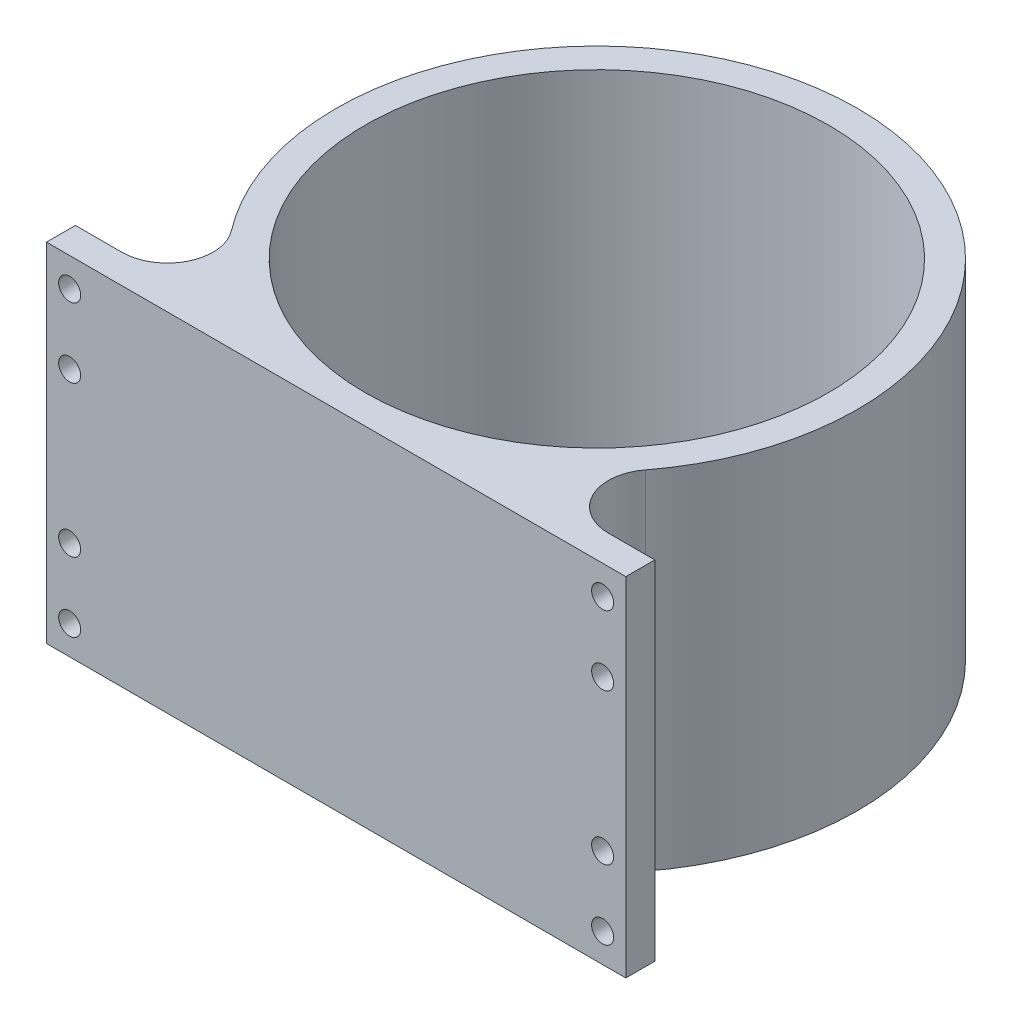
SolidWorks part; units mm, degrees
ref_plane "Front Plane" through (0, 0, 0) normal (0, 0, 1) x (1, 0, 0)
ref_plane "Top Plane" through (0, 0, 0) normal (0, 1, 0) x (1, 0, 0)
ref_plane "Right Plane" through (0, 0, 0) normal (1, 0, 0) x (0, 0, -1)
sketch "Sketch1" plane through (0, 0, 0) normal (0, 1, 0) x (1, 0, 0)
  line L0 (0, 0) -> (0, -57.15) construction
  line L1 (0, -57.15) -> (63.5, -57.15) construction
  line L3 (63.5, -57.15) -> (-63.5, -57.15)
  line L4 (63.5, -57.15) -> (63.5, -50.8)
  line L5 (63.5, -50.8) -> (-63.5, -50.8)
  line L6 (-63.5, -57.15) -> (-63.5, -50.8)
  circle A0 centre (0, 0) radius 57.15
  circle A1 centre (0, 0) radius 50.8
  point P9 (0, -57.15)
  point P10 (0, 0)
  point P11 (0, -57.15)
  point P12 (0, -57.15)
  dimension "D1" = 114.3
  dimension "D2" = 101.6
  dimension "D3" = 63.5
  dimension "D4" = 127
  dimension "D5" = 6.35
extrude "Boss-Extrude1" add sketch "Sketch1" along normal blind 76.2 contours A0 A1 | A0 L5 L6 L3 | A0 L5 | A0 L3 L4 L5
fillet "Fillet3" radius 10 2 edges at (-26.1817, 38.1, 50.8) (26.1817, 38.1, 50.8)
sketch "Sketch2" plane through (0, 0, 50.8) normal (0, 0, -1) x (-1, 0, 0)
  line L0 (-58.4168, 0) -> (-58.4168, 76.2) construction
  line L1 (-63.5, 0) -> (-53.3337, 0) construction
  line L2 (-63.5, 76.2) -> (-53.3337, 76.2) construction
  line L3 (58.4168, 0) -> (58.4168, 76.2) construction
  line L4 (53.3337, 0) -> (63.5, 0) construction
  line L5 (53.3337, 76.2) -> (63.5, 76.2) construction
  line L6 (0, 0) -> (0, 76.2) construction
  line L7 (50.8, 76.2) -> (-50.8, 76.2) construction
  circle A0 centre (58.4168, 6.35) radius 2.413
  circle A1 centre (58.4168, 21.59) radius 2.413
  circle A2 centre (58.4168, 69.85) radius 2.413
  circle A3 centre (58.4168, 54.61) radius 2.413
  circle A4 centre (-58.4168, 6.35) radius 2.413
  circle A5 centre (-58.4168, 21.59) radius 2.413
  circle A6 centre (-58.4168, 69.85) radius 2.413
  circle A7 centre (-58.4168, 54.61) radius 2.413
  point P20 (0, 92.714)
  dimension "D1" = 4.826
  dimension "D2" = 6.35
  dimension "D3" = 6.35
  dimension "D4" = 15.24
  dimension "D5" = 15.24
extrude "Cut-Extrude1" cut sketch "Sketch2" against normal through all
sketch "Sketch3" plane through (0, 0, 0) normal (1, 0, 0) x (0, 0, -1)
  line L0 (0, 0) -> (0, 76.2) construction
  line L2 (57.15, 76.2) -> (-34.7241, 76.2) construction
  point P5 (0, 89.2825)
